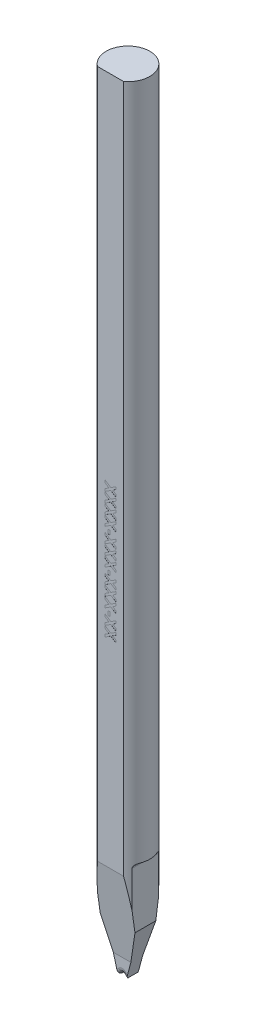
SolidWorks part; units mm, degrees
ref_plane "Ebene vorne" through (0, 0, 0) normal (0, 0, 1) x (1, 0, 0)
ref_plane "Ebene oben" through (0, 0, 0) normal (0, 1, 0) x (1, 0, 0)
ref_plane "Ebene rechts" through (0, 0, 0) normal (1, 0, 0) x (0, 0, -1)
sketch "sketch_TL_cutting" plane through (0, 0, 0) normal (0, 1, 0) x (1, 0, 0)
  circle A0 centre (0, 0) radius 1.9977
extrude "TL_cutting" add sketch "sketch_TL_cutting" along normal blind 72.009
sketch "sketch_TDF_grinding" plane through (0, 0, 0) normal (0, 1, 0) x (1, 0, 0)
  line L0 (0, 0) -> (0, -1.6015) construction
  line L1 (-2.0077, -5.6169) -> (2.0077, -5.6169)
  line L2 (-2.0077, -5.6169) -> (-2.0077, -1.6015)
  line L3 (-2.0077, -1.6015) -> (2.0077, -1.6015)
  line L4 (2.0077, -5.6169) -> (2.0077, -1.6015)
  circle A1 centre (0, 0) radius 1.9977 construction
  point P9 (0, -5.6169)
  dimension "TD_2Offset_X" = 4.0154
  dimension "TD_2Offset_Z" = 4.0154
extrude "TDF_grinding" cut sketch "sketch_TDF_grinding" along normal through all
sketch "sketch_engraving" plane through (0, 0, 1.6015) normal (0, 0, 1) x (1, 0, 0)
  line L0 (1.1942, 72.009) -> (-1.1942, 72.009) construction
  line L6 (-1.1942, 0) -> (1.1942, 0) construction
  line L7 (0, 0) -> (0, 39.605) construction
  line L8 (-0.5, 39.605) -> (-0.5, 0) construction
  text T0 "XXXX-XXX-XXX-XX" font "Arial" height 1
  dimension "D2" = 0.5
  dimension "EngravingStart" = 32.404
extrude "engraving" cut sketch "sketch_engraving" against normal blind 0.005
sketch "sketch_VW_VR_grinding" plane through (0, 0, 0) normal (0, 0, 1) x (1, 0, 0)
  line L0 (-1.59, -0.01) -> (-1.59, 9.682)
  line L1 (1.59, -0.01) -> (1.59, 9.682)
  line L2 (-1.59, 0) -> (1.59, 0) construction
  line L3 (-2.0077, 10) -> (-1.908, 10)
  line L4 (1.908, 10) -> (2.0077, 10)
  line L5 (-2.0077, 10) -> (-2.0077, -0.01)
  line L6 (-2.0077, -0.01) -> (-1.59, -0.01)
  line L7 (1.59, -0.01) -> (2.0077, -0.01)
  line L8 (2.0077, -0.01) -> (2.0077, 10)
  line L9 (-1.908, 10) -> (-1.908, 9.682) construction
  line L10 (-1.59, 9.682) -> (-1.908, 9.682) construction
  line L11 (1.59, 9.682) -> (1.908, 9.682) construction
  line L12 (1.908, 10) -> (1.908, 9.682) construction
  arc A0 (-1.908, 10) -> (-1.59, 9.682) centre (-1.908, 9.682) cw
  arc A2 (1.59, 9.682) -> (1.908, 10) centre (1.908, 9.682) cw
  dimension "D1" = 0.01
  dimension "D4" = 4.0154
extrude "VW_VR_grinding" cut sketch "sketch_VW_VR_grinding" against normal blind 2.0077 and the other way blind 2.0077
sketch "sketch_ISA_grinding" plane through (0, 0, 0) normal (0, 0, 1) x (1, 0, 0)
  line L0 (-0.4001, 0) -> (-2.0077, 5.9999)
  line L4 (2.0077, 5.9999) -> (0.4001, 0)
  line L5 (0.4001, 0) -> (-0.4001, 0)
  line L6 (0, 0) -> (0, 30.49) construction
  line L7 (-2.0077, 5.9999) -> (-2.0077, -0.01)
  line L12 (-2.0077, -0.01) -> (2.0077, -0.01)
  line L13 (2.0077, -0.01) -> (2.0077, 5.9999)
  dimension "ISA" = 30
  dimension "TD_2Offset" = 4.0154
  dimension "Offset" = 0.01
extrude "ISA_grinding" cut sketch "sketch_ISA_grinding" against normal blind 2.0077 and the other way blind 2.0077
sketch "sketch_pre_FRX_BRX" plane through (0, 0, 0) normal (1, 0, 0) x (0, 0, -1)
  line L0 (1.9977, -0.01) -> (1.9977, 3.9152) construction
  line L1 (-1.6015, -0.01) -> (-1.6015, 1.4886) construction
  line L2 (-0.5397, -0.01) -> (-0.5397, 1.4886)
  line L3 (-0.5397, 1.4886) -> (-2.0077, 1.4886)
  line L4 (-2.0077, 1.4886) -> (-2.0077, -0.01)
  line L5 (-2.0077, -0.01) -> (-0.5397, -0.01)
  line L6 (0.5398, -0.01) -> (0.5398, 1.4886)
  line L7 (0.5398, 1.4886) -> (2.0077, 1.4886)
  line L8 (2.0077, 1.4886) -> (2.0077, -0.01)
  line L9 (2.0077, -0.01) -> (0.5398, -0.01)
  dimension "D3" = 0.01
  dimension "D4" = 1.4986
  dimension "D5" = 4.0154
  dimension "D6" = 1.0795
  dimension "D2" = 0.01
  dimension "D7" = 2.5375
extrude "pre_FRX_BRX" cut sketch "sketch_pre_FRX_BRX" against normal blind 2.0077 and the other way blind 2.0077
sketch "sketch_contour_V-Groove" plane through (0, 0, 0) normal (1, 0, 0) x (0, 0, -1)
  line L0 (-1.6015, 0.2286) -> (0, 0.2286)
  line L1 (0, 0.2286) -> (1.9977, 0.2286)
  line L2 (1.9977, -0.8411) -> (1.9977, 1.3178) construction
  line L3 (-1.6015, -0.9209) -> (-1.6015, 1.9363) construction
  line L4 (-1.6015, 0) -> (1.9977, 0) construction
  line L5 (0.5398, 0) -> (0.5398, 0.2286) construction
  line L6 (-0.5397, 0) -> (-0.5397, 0.2286) construction
  dimension "D1" = 0
ref_plane "front" through (0, 0, 1.6015) normal (0, 0, 1) x (1, 0, 0)
ref_plane "back" through (0, 0, -1.9977) normal (0, 0, 1) x (1, 0, 0)
sketch "sketch_section_V-Groove" plane through (0, 0, 1.6015) normal (0, 0, 1) x (1, 0, 0)
  line L0 (-2.5311, -2.286) -> (-0.0282, 0.2169)
  line L2 (0.0282, 0.2169) -> (2.5311, -2.286)
  line L3 (-2.5311, -2.286) -> (2.5311, -2.286)
  line L4 (0, -2.286) -> (0, 0.2286) construction
  line L5 (-0.2451, 0) -> (0.2451, 0) construction
  arc A0 (0.0282, 0.2169) -> (-0.0282, 0.2169) centre (0, 0.1887) ccw
  dimension "GA" = 90
sweep "V-Groove_EDM" cut profiles "sketch_section_V-Groove" path "sketch_contour_V-Groove"
fillet "FR_EDM" radius 0.3988 3 edges at (0.1366, 0.1085, 0.5397) (0, 0.2286, 0.5397) (-0.1366, 0.1085, 0.5397)
fillet "BR_EDM" radius 0.2007 3 edges at (0.1366, 0.1085, -0.5398) (0, 0.2286, -0.5398) (-0.1366, 0.1085, -0.5398)
sketch "sketch_FA_BA_grinding" plane through (0, 0, 0) normal (1, 0, 0) x (0, 0, -1)
  line L2 (2.9977, 18.9879) -> (2.9977, -0.1)
  line L3 (2.9977, -0.1) -> (0.5398, -0.1)
  line L5 (0.5398, -0.1) -> (0.5398, 1.4986)
  line L6 (0.5398, 1.4986) -> (2.9977, 18.9879)
  line L7 (1.9977, -0.1) -> (1.9977, 11.8725) construction
  line L8 (-1.6015, 9.0531) -> (-1.6015, -0.1) construction
  line L9 (-3.4875, 22.4726) -> (-0.5397, 1.4986)
  line L10 (-0.5397, 1.4986) -> (-0.5397, -0.1)
  line L11 (-0.5397, -0.1) -> (-3.4875, -0.1)
  line L12 (-3.4875, -0.1) -> (-3.4875, 22.4726)
  line L13 (-0.5397, 1.4986) -> (0.5398, 1.4986) construction
  dimension "D4" = 1
  dimension "D1" = 0.1
  dimension "FA" = 8
  dimension "BA" = 8
extrude "FA_BA_grinding" cut sketch "sketch_FA_BA_grinding" against normal blind 2.0077 and the other way blind 2.0077
sketch "sketch_groove_dimensions" plane through (0, 0, 0) normal (1, 0, 0) x (0, 0, -1)
  line L0 (-0.141, 0.2286) -> (0.3391, 0.2286)
  line L1 (-0.5397, 0) -> (-0.5397, 0.6274) construction
  line L2 (1.9977, 0) -> (1.9977, 0.4166) construction
  line L3 (0.5398, 0) -> (0.5398, 0.4293) construction
  line L4 (-1.6015, 0) -> (-1.6015, 0.3999) construction
  arc A0 (0.3391, 0.2286) -> (0.5398, 0.4293) centre (0.3391, 0.4293) ccw
  arc A1 (-0.141, 0.2286) -> (-0.5397, 0.6274) centre (-0.141, 0.6274) cw
equation "\"_Offset\"=0.01mm"
equation "\"TL\"=72.009mm"
equation "\"TD\"=3.99542mm"
equation "\"TDF\"=3.59918mm"
equation "\"BA\"=8deg"
equation "\"ISA\"=30deg"
equation "\"FA\"=8deg"
equation "\"GR\"=0.04064mm"
equation "\"GA\"=90deg"
equation "\"GD\"=0.2286mm"
equation "\"FL\"=1.0795mm"
equation "\"F\"=0.48006mm"
equation "\"FX\"=0mm"
equation "\"B\"=0.49022mm"
equation "\"VW\"=3.18008mm"
equation "\"cleaned_VR\"= IIF ( \"VR\" > 0 , \"VR\" , \"E\" - \"_Offset\" )"
equation "\"cleaned_VW\"= IIF ( \"VW\" > 0 , \"VW\" , \"TD\" - \"_Offset\" )"
equation "\"back_edge\"= \"TD\" / 2 - \"X\""
equation "\"side_edge_Offset\"= \"TD\" / 2 + \"_Offset\""
equation "\"TD@sketch_TL_cutting\"=\"TD\""
equation "\"TL@TL_cutting\"=\"TL\""
equation "\"TDF@sketch_TDF_grinding\"=\"TDF\""
equation "\"TD_2Offset_X@sketch_TDF_grinding\"=\"TD\"+2*\"_Offset\""
equation "\"TD_2Offset_Z@sketch_TDF_grinding\"=\"TD\"+2*\"_Offset\""
equation "\"TL_Offset\"= \"TL\" + \"_Offset\""
equation "\"ISA@sketch_ISA_grinding\"=\"ISA\""
equation "\"W@sketch_ISA_grinding\"=\"W\""
equation "\"TD_2Offset@sketch_ISA_grinding\"=\"TD\"+2*\"_Offset\""
equation "\"Offset@sketch_ISA_grinding\"=\"_Offset\""
equation "\"05TD_Offset_posZ@ISA_grinding\"=\"side_edge_Offset\""
equation "\"05TD_Offset_negZ@ISA_grinding\"=\"side_edge_Offset\""
equation "\"E\"=1.4986mm"
equation "\"cleaned_X\"= IIF ( \"X\" > 0 , \"X\" , \"TD\" / 2 - \"FL\" / 2 )"
equation "\"FR\"=0.39878mm"
equation "\"BR\"=0.20066mm"
equation "\"D1\"= \"side_edge_Offset\""
equation "\"D2\"= \"side_edge_Offset\""
equation "\"TDF@sketch_FA_BA_grinding\" = \"TDF\""
equation "\"FL@sketch_FA_BA_grinding\"=\"FL\""
equation "\"E@sketch_FA_BA_grinding\" = \"E\""
equation "\"D1@FA_BA_grinding\"=\"side_edge_Offset\""
equation "\"D2@FA_BA_grinding\"=\"side_angle_Offset\""
equation "\"10GD@sketch_section_V-Groove\" = 10 * \"GD\""
equation "\"GA@sketch_section_V-Groove\" = \"GA\""
equation "\"GD@sketch_section_V-Groove\" = \"GD\""
equation "\"B@sketch_section_V-Groove\" = \"B\""
equation "\"GD@sketch_contour_V-Groove\" = \"GD\""
equation "\"cleaned_FRX\"= IIF ( \"FRX\" > 0 , \"FRX\" , \"FR\" )"
equation "\"cleaned_BRX\"= IIF ( \"BRX\" > 0 , \"BRX\" , \"BR\" )"
equation "\"FL_groove_angle\"=0deg"
equation "\"D3@sketch_pre_FRX_BRX\" = \"_Offset\""
equation "\"D4@sketch_pre_FRX_BRX\" = \"E\""
equation "\"D5@sketch_pre_FRX_BRX\" = 2 * \"side_edge_Offset\""
equation "\"D6@sketch_pre_FRX_BRX\" = \"FL\" + ( \"FR\" - \"cleaned_FRX\" ) + ( \"BR\" - \"cleaned_BRX\" )"
equation "\"TD/2@sketch_pre_FRX_BRX\" = \"TD\" / 2"
equation "\"TDF@sketch_pre_FRX_BRX\" = \"TDF\""
equation "\"D2@sketch_pre_FRX_BRX\" = \"_Offset\""
equation "\"D1@pre_FRX_BRX\" = \"side_edge_Offset\""
equation "\"D2@pre_FRX_BRX\" = \"side_edge_Offset\""
equation "\"D1@BR_EDM\"=\"BR\""
equation "\"TD/2@sketch_FA_BA_grinding\" = \"TD\" / 2"
equation "\"TD/2@sketch_contour_V-Groove\" = \"TD\" / 2"
equation "\"TDF@sketch_contour_V-Groove\" = \"TDF\""
equation "\"D1@sketch_contour_V-Groove\"=\"FL_groove_angle\""
equation "\"FL@sketch_contour_V-Groove\"=\"FL\""
equation "\"FL/2@sketch_contour_V-Groove\" = \"FL\" / 2"
equation "\"D1@FR_EDM\"=\"FR\""
equation "\"D1@sketch_VW_VR_grinding\" = \"_Offset\""
equation "\"D4@sketch_VW_VR_grinding\" = 2 * \"side_edge_Offset\""
equation "\"VR@sketch_VW_VR_grinding\" = \"cleaned_VR\""
equation "\"VW@sketch_VW_VR_grinding\"=\"cleaned_VW\""
equation "\"D1@VW_VR_grinding\" = \"side_edge_Offset\""
equation "\"D2@VW_VR_grinding\" = \"side_edge_Offset\""
equation "\"X\"=0.94996mm"
equation "\"VR\"=9.99998mm"
equation "\"W\"=0.8001mm"
equation "\"VW_radius\"= \"cleaned_VW\" / 10"
equation "\"VW_radius_cleaned\"= IIF ( \"VW\" > 0 , \"VW_radius\" , \"_Offset\" / 2 )"
equation "\"D2@sketch_VW_VR_grinding\"=\"VW_radius_cleaned\""
equation "\"FRX\"=0mm"
equation "\"BRX\"=0mm"
equation "\"FA@sketch_FA_BA_grinding\" = \"FA\""
equation "\"D4@sketch_FA_BA_grinding\"=\"_Offset\"*100"
equation "\"BA@sketch_FA_BA_grinding\" = \"BA\""
equation "\"D1@sketch_groove_dimensions\" = \"TD\" / 2"
equation "\"FL@sketch_groove_dimensions\" = \"FL\""
equation "\"FR@sketch_groove_dimensions\" = \"FR\""
equation "\"BR@sketch_groove_dimensions\" = \"BR\""
equation "\"FRX@sketch_groove_dimensions\" = \"cleaned_FRX\""
equation "\"BRX@sketch_groove_dimensions\" = \"cleaned_BRX\""
equation "\"GD@sketch_groove_dimensions\" = \"GD\""
equation "\"cleaned_FX\"= IIF ( \"FX\" > 0 , \"FX\" , \"TDF\" - ( \"TD\" + \"FL\" ) / 2 )"
equation "\"D7@sketch_pre_FRX_BRX\"=\"TDF\"-\"cleaned_FX\"-(\"FR\"-\"cleaned_FRX\")"
equation "\"FX@sketch_contour_V-Groove\" = \"cleaned_FX\""
equation "\"FX@sketch_FA_BA_grinding\" = \"cleaned_FX\""
equation "\"TDF@sketch_groove_dimensions\" = \"TDF\""
equation "\"FX@sketch_groove_dimensions\" = \"cleaned_FX\""
equation "\"EngravingStart\" = \"TL\" * 0.45"
equation "\"EngravingStart@sketch_engraving\" = \"EngravingStart\""
